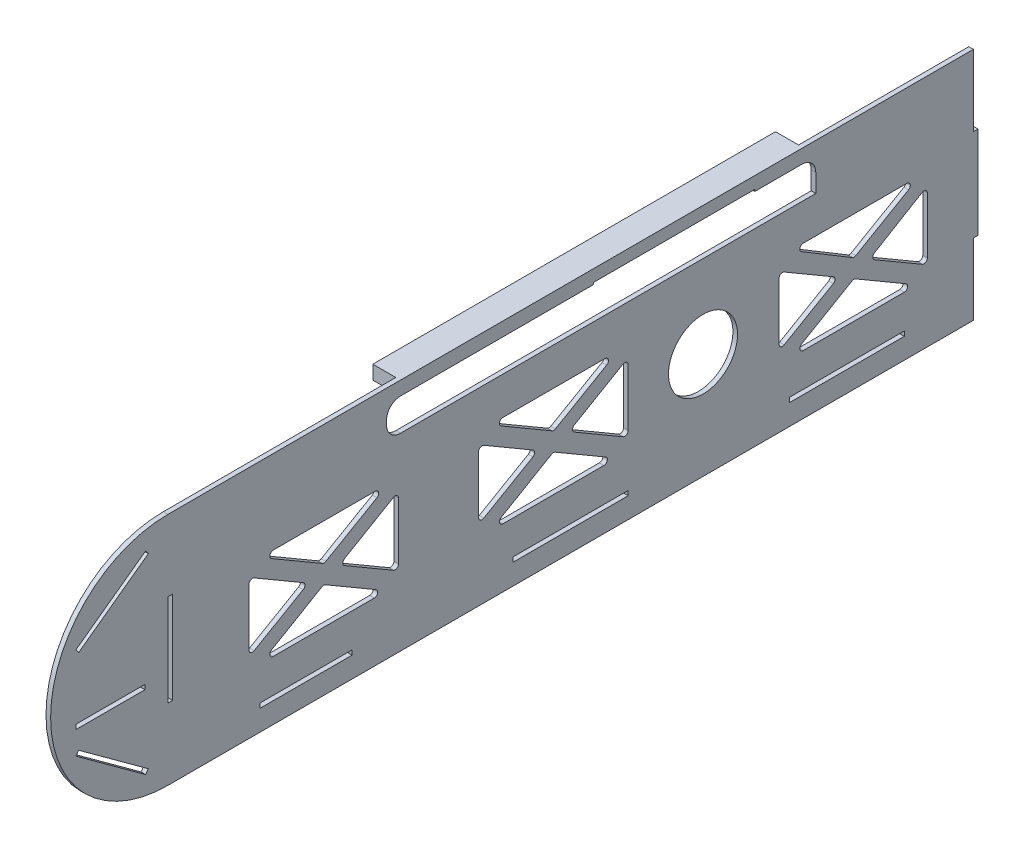
SolidWorks part; units mm, degrees
ref_plane "前视基准面" through (0, 0, 0) normal (0, 0, 1) x (1, 0, 0)
ref_plane "上视基准面" through (0, 0, 0) normal (0, 1, 0) x (1, 0, 0)
ref_plane "右视基准面" through (0, 0, 0) normal (1, 0, 0) x (0, 0, -1)
sketch "草图1" plane through (0, 0, 0) normal (1, 0, 0) x (0, 0, -1)
  line L0 (95, 39) -> (95, 37)
  line L1 (0, 51) -> (139, 51)
  line L2 (0, 51) -> (0, -51)
  line L3 (0, -51) -> (350, -51)
  line L4 (350, 51) -> (350, -51)
  line L5 (145, 51) -> (281.5, 51)
  line L6 (101, 31) -> (275.5, 31)
  line L7 (281.5, 39) -> (281.5, 36)
  line L8 (337.5, 51) -> (350, 51)
  line L10 (-40, -10) -> (-10, -10)
  line L11 (-40, -10) -> (-40, -8)
  line L12 (-40, -8) -> (-10, -8)
  line L13 (-10, -10) -> (-10, -8)
  line L22 (145.5484, 14.6595) -> (189.8851, 14.6595)
  line L23 (135, 7.0479) -> (135, -17.7392)
  line L24 (145.5484, -25.3405) -> (189.4516, -25.3405)
  line L25 (200, 7.3884) -> (200, -17.3884)
  line L29 (176.5069, -6.2957) -> (197.7442, -18.6841)
  line L30 (158.585, -4.0984) -> (137.2558, 8.3436)
  line L31 (137.2514, -19.0374) -> (158.5806, -6.6923)
  line L32 (176.5069, -3.7043) -> (197.7442, 8.6841)
  line L33 (144.7926, 11.8638) -> (166.8743, -1.0172)
  line L34 (190.6365, 11.8613) -> (168.3815, -1.0197)
  line L35 (168.2558, -9.7397) -> (190.2074, -22.5448)
  line L36 (144.7926, -22.5448) -> (166.7442, -9.7397)
  line L37 (276.0709, 15) -> (321.089, 15)
  line L38 (265.5225, 6.9941) -> (265.5225, -17.793)
  line L39 (276.0709, -25.3943) -> (319.9742, -25.3943)
  line L40 (330, 6.9941) -> (330, -17.478)
  line L41 (307.0294, -6.69) -> (327.7442, -18.7736)
  line L42 (289.1076, -4.1523) -> (267.7784, 8.2898)
  line L43 (267.7739, -19.0912) -> (289.1032, -6.7462)
  line L44 (307.0153, -4.107) -> (327.7301, 8.2815)
  line L45 (275.2981, 12.2144) -> (297.3797, -1.0609)
  line L46 (321.8404, 12.2018) -> (298.904, -1.0735)
  line L47 (298.7784, -9.7935) -> (320.73, -22.5987)
  line L48 (275.3151, -22.5987) -> (297.2667, -9.7935)
  line L49 (-40, 20) -> (-9.6982, 42.0918)
  line L50 (-40, 20) -> (-38.8218, 18.3839)
  line L51 (-9.6982, 42.0918) -> (-8.5199, 40.4757)
  line L52 (-38.8218, 18.3839) -> (-8.5199, 40.4757)
  line L53 (-51, 0) -> (0, 0)
  line L54 (-38.8218, -18.3839) -> (-8.5199, -40.4757)
  line L55 (-9.6982, -42.0918) -> (-8.5199, -40.4757)
  line L56 (-40, -20) -> (-38.8218, -18.3839)
  line L57 (-40, -20) -> (-9.6982, -42.0918)
  line L58 (40, -40) -> (80, -40)
  line L59 (40, -40) -> (40, -42)
  line L60 (80, -40) -> (80, -42)
  line L61 (40, -42) -> (80, -42)
  line L62 (150, -40) -> (200, -40)
  line L63 (150, -40) -> (150, -42)
  line L64 (200, -40) -> (200, -42)
  line L65 (150, -42) -> (200, -42)
  line L66 (270, -40) -> (320, -40)
  line L67 (270, -40) -> (270, -42)
  line L68 (320, -40) -> (320, -42)
  line L69 (270, -42) -> (320, -42)
  line L70 (350, 20) -> (352, 20)
  line L71 (350, 20) -> (350, -20)
  line L72 (352, 20) -> (352, -20)
  line L73 (350, -20) -> (352, -20)
  line L74 (0, 20) -> (0, -20)
  line L75 (0, 20) -> (2, 20)
  line L76 (0, -20) -> (2, -20)
  line L77 (2, 20) -> (2, -20)
  line L78 (139, 51) -> (145, 51)
  line L79 (281.5, 51) -> (337.5, 51)
  line L80 (101, 45) -> (275.5, 45)
  line L81 (101, 31) -> (101, 45)
  line L82 (281.5, 36) -> (281.5, 31)
  line L83 (45.7401, 14.6595) -> (90.0769, 14.6595)
  line L84 (35.1917, 7.0479) -> (35.1917, -17.7392)
  line L85 (275.5, 31) -> (281.5, 31)
  line L86 (45.7401, -25.3405) -> (89.6434, -25.3405)
  line L87 (185, 45) -> (255, 45)
  line L88 (185, 45) -> (185, 45.8)
  line L89 (185, 45.8) -> (255, 45.8)
  line L90 (255, 45) -> (255, 45.8)
  line L91 (100.1917, 7.0479) -> (100.1917, -17.729)
  line L92 (76.6986, -6.6362) -> (97.9359, -19.0246)
  line L93 (58.7768, -4.0984) -> (37.4476, 8.3436)
  line L94 (37.4431, -19.0374) -> (58.7724, -6.6923)
  line L95 (76.6986, -4.0448) -> (97.9359, 8.3436)
  line L96 (44.9843, 11.8638) -> (67.066, -1.0172)
  line L97 (90.8283, 11.8613) -> (68.5732, -1.0197)
  line L98 (68.4476, -9.7397) -> (90.3992, -22.5448)
  line L99 (44.9843, -22.5448) -> (66.9359, -9.7397)
  arc A0 (0, 51) -> (0, -51) centre (0, 0) ccw
  arc A1 (97.9359, 8.3436) -> (100.1917, 7.0479) centre (98.6917, 7.0479) cw
  arc A3 (101, 31) -> (95, 37) centre (101, 37) cw
  arc A4 (100.1917, -17.729) -> (97.9359, -19.0246) centre (98.6917, -17.729) cw
  arc A17 (197.7442, 8.6841) -> (200, 7.3884) centre (198.5, 7.3884) cw
  arc A18 (200, -17.3884) -> (197.7442, -18.6841) centre (198.5, -17.3884) cw
  arc A19 (176.5069, -6.2957) -> (176.5069, -3.7043) centre (177.2627, -5) cw
  arc A20 (158.585, -4.0984) -> (158.5806, -6.6923) centre (157.8292, -5.3941) cw
  arc A21 (137.2514, -19.0374) -> (135, -17.7392) centre (136.5, -17.7392) cw
  arc A22 (135, 7.0479) -> (137.2558, 8.3436) centre (136.5, 7.0479) cw
  arc A23 (144.7926, -22.5448) -> (145.5484, -25.3405) centre (145.5484, -23.8405) ccw
  arc A24 (189.4516, -25.3405) -> (190.2074, -22.5448) centre (189.4516, -23.8405) ccw
  arc A25 (168.2558, -9.7397) -> (166.7442, -9.7397) centre (167.5, -11.0354) ccw
  arc A26 (144.7926, 11.8638) -> (145.5484, 14.6595) centre (145.5484, 13.1595) cw
  arc A27 (189.8851, 14.6595) -> (190.6365, 11.8613) centre (189.8851, 13.1595) cw
  arc A28 (168.3815, -1.0197) -> (166.8743, -1.0172) centre (167.6301, 0.2785) cw
  arc A29 (327.7301, 8.2815) -> (330, 6.9941) centre (328.5, 6.9941) cw
  arc A30 (330, -17.478) -> (327.7442, -18.7736) centre (328.5, -17.478) cw
  arc A31 (307.0294, -6.69) -> (307.0153, -4.107) centre (307.7852, -5.3943) cw
  arc A32 (289.1076, -4.1523) -> (289.1032, -6.7462) centre (288.3518, -5.4479) cw
  arc A33 (267.7739, -19.0912) -> (265.5225, -17.793) centre (267.0225, -17.793) cw
  arc A34 (265.5225, 6.9941) -> (267.7784, 8.2898) centre (267.0225, 6.9941) cw
  arc A35 (275.3151, -22.5987) -> (276.0709, -25.3943) centre (276.0709, -23.8943) ccw
  arc A36 (319.9742, -25.3943) -> (320.73, -22.5987) centre (319.9742, -23.8943) ccw
  arc A37 (298.7784, -9.7935) -> (297.2667, -9.7935) centre (298.0225, -11.0892) ccw
  arc A38 (275.2981, 12.2144) -> (276.0709, 15) centre (276.0709, 13.5) cw
  arc A39 (321.089, 15) -> (321.8404, 12.2018) centre (321.089, 13.5) cw
  arc A40 (298.904, -1.0735) -> (297.3797, -1.0609) centre (298.1526, 0.2247) cw
  circle A41 centre (232.5, -5) radius 15
  arc A43 (76.6986, -6.6362) -> (76.6986, -4.0448) centre (77.4544, -5.3405) cw
  arc A44 (281.5, 39) -> (275.5, 45) centre (275.5, 39) ccw
  arc A45 (101, 45) -> (95, 39) centre (101, 39) ccw
  arc A46 (58.7768, -4.0984) -> (58.7724, -6.6923) centre (58.021, -5.3941) cw
  arc A47 (37.4431, -19.0374) -> (35.1917, -17.7392) centre (36.6917, -17.7392) cw
  arc A48 (35.1917, 7.0479) -> (37.4476, 8.3436) centre (36.6917, 7.0479) cw
  arc A49 (44.9843, -22.5448) -> (45.7401, -25.3405) centre (45.7401, -23.8405) ccw
  arc A50 (89.6434, -25.3405) -> (90.3992, -22.5448) centre (89.6434, -23.8405) ccw
  arc A51 (68.4476, -9.7397) -> (66.9359, -9.7397) centre (67.6917, -11.0354) ccw
  arc A52 (44.9843, 11.8638) -> (45.7401, 14.6595) centre (45.7401, 13.1595) cw
  arc A53 (90.0769, 14.6595) -> (90.8283, 11.8613) centre (90.0769, 13.1595) cw
  arc A54 (68.5732, -1.0197) -> (67.066, -1.0172) centre (67.8218, 0.2785) cw
  point P5 (40.1917, 14.6595)
  point P7 (281.5, 31)
  point P8 (286.5, 50)
  point P21 (95, 31)
  point P24 (95.6629, 14.6595)
  point P28 (40.1917, -25.3405)
  point P29 (95.1917, -25.3405)
  point P30 (40.1917, -25.3405)
  point P31 (35.1917, -20.3405)
  point P32 (100, 30)
  point P33 (100.1917, -20.3405)
  point P34 (100.1917, 9.6595)
  point P35 (35.1917, 9.6595)
  point P53 (140, 14.6595)
  point P58 (195.4712, 14.6595)
  point P59 (140, -25.3405)
  point P60 (195, -25.3405)
  point P61 (140, -25.3405)
  point P62 (135, -20.3405)
  point P63 (200, -20)
  point P64 (200, 10)
  point P65 (135, 9.6595)
  point P124 (270.5225, 15)
  point P129 (325.9937, 15)
  point P130 (270.5225, -25.3943)
  point P131 (325.5225, -25.3943)
  point P132 (270.5225, -25.3943)
  point P133 (265.5225, -20.3943)
  point P134 (330, -20.3943)
  point P135 (330, 9.6057)
  point P136 (265.5225, 9.6057)
  point P169 (350, -20)
  point P182 (-9.6982, -42.0918)
  point P184 (-40, -20)
  point P189 (352, 20)
  point P190 (352, -20)
  point P198 (350, 20)
  dimension "D5" = 1.5
  dimension "D6" = 1.5
  dimension "D7" = 1.5
  dimension "D8" = 1.5
  dimension "D9" = 1.5
  dimension "D10" = 1.5
  dimension "D11" = 1.5
  dimension "D12" = 1.5
  dimension "D13" = 1.5
  dimension "D14" = 1.5
  dimension "D15" = 1.5
  dimension "D16" = 1.5
  dimension "D17" = 1.5
  dimension "D18" = 1.5
  dimension "D19" = 1.5
  dimension "D20" = 1.5
  dimension "D21" = 1.5
  dimension "D22" = 1.5
  dimension "D23" = 1.5
  dimension "D24" = 1.5
  dimension "D25" = 1.5
  dimension "D26" = 1.5
  dimension "D27" = 1.5
  dimension "D28" = 1.5
  dimension "D29" = 1.5
  dimension "D30" = 1.5
  dimension "D31" = 1.5
  dimension "D32" = 1.5
  dimension "D33" = 1.5
  dimension "D34" = 1.5
  dimension "D35" = 1.5
  dimension "D36" = 1.5
  dimension "D37" = 1.5
  dimension "D38" = 1.5
  dimension "D39" = 1.5
  dimension "D40" = 1.5
  dimension "D41" = 2
  dimension "D42" = 37.5
  dimension "D43" = 2
extrude "凸台-拉伸3" add sketch "草图1" along normal blind 2 contours L79 L5 L78 L1 L2 L75 L77 L76 L3 L4 L8 A51 L98 A50 L86 A49 L99 A45 L80 L88 L89 L90 A44 L7 L82 L85 L6 A3 L0 A41 A37 L47 A36 L39 A35 L48 A25 L35 A24 L24 A23 L36 | L2 A0 L53 L52 L50 L49 L51 | L53 A0 L2 L57 L56 L54 L55 L13 L10 L11 L12 | L70 L71 L73 L72
sketch "草图2" plane through (0, 0, 0) normal (1, 0, 0) x (0, 0, -1)
  line L31 (101, 45) -> (101, 51)
  line L32 (101, 45) -> (276, 45)
  line L33 (101, 51) -> (276, 51)
  line L34 (276, 45) -> (276, 51)
  line L35 (0, 51) -> (350, 51) construction
  line L36 (185, 45) -> (185, 45.8)
  line L37 (185, 45) -> (255, 45)
  line L38 (185, 45.8) -> (255, 45.8)
  line L39 (255, 45) -> (255, 45.8)
extrude "凸台-拉伸4" add sketch "草图2" against normal blind 10
